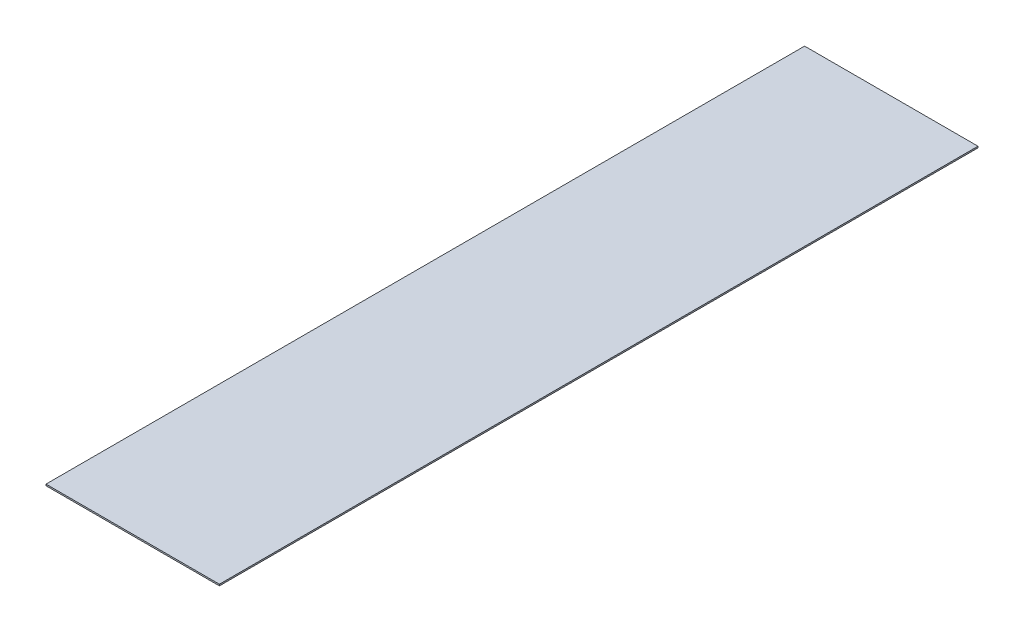
SolidWorks part; units mm, degrees
ref_plane "Alzado" through (0, 0, 0) normal (0, 0, 1) x (1, 0, 0)
ref_plane "Planta" through (0, 0, 0) normal (0, 1, 0) x (1, 0, 0)
ref_plane "Vista lateral" through (0, 0, 0) normal (1, 0, 0) x (0, 0, -1)
sketch "Croquis1" plane through (0, 0, 0) normal (0, 1, 0) x (1, 0, 0)
  line L1 (0, 0) -> (400, 0)
  line L2 (0, 0) -> (0, 1750)
  line L3 (0, 1750) -> (400, 1750)
  line L4 (400, 0) -> (400, 1750)
  dimension "D1" = 400
  dimension "D2" = 1750
extrude "Saliente-Extruir1" add sketch "Croquis1" along normal blind 3.4163
